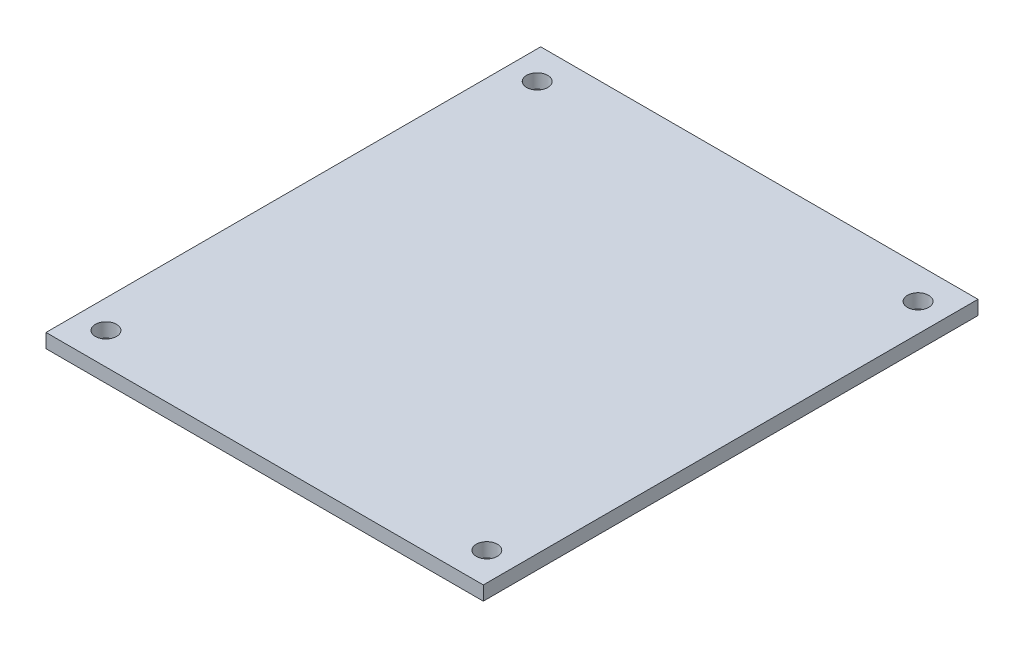
SolidWorks part; units mm, degrees
ref_plane "Спереди" through (0, 0, 0) normal (0, 0, 1) x (1, 0, 0)
ref_plane "Сверху" through (0, 0, 0) normal (0, 1, 0) x (1, 0, 0)
ref_plane "Справа" through (0, 0, 0) normal (1, 0, 0) x (0, 0, -1)
sketch "Эскиз1" plane through (0, 0, 0) normal (0, 1, 0) x (1, 0, 0)
  line L1 (-26.3454, 47.7896) -> (35.6546, 47.7896)
  line L2 (-26.3454, 47.7896) -> (-26.3454, -22.3504)
  line L3 (-26.3454, -22.3504) -> (35.6546, -22.3504)
  line L4 (35.6546, 47.7896) -> (35.6546, -22.3504)
  circle A0 centre (-22.3454, 43.2896) radius 1.5
  circle A1 centre (31.6546, 43.2896) radius 1.5
  circle A2 centre (31.6546, -17.8504) radius 1.5
  circle A3 centre (-22.3454, -17.8504) radius 1.5
extrude "Бобышка-Вытянуть1" add sketch "Эскиз1" along normal blind 2
